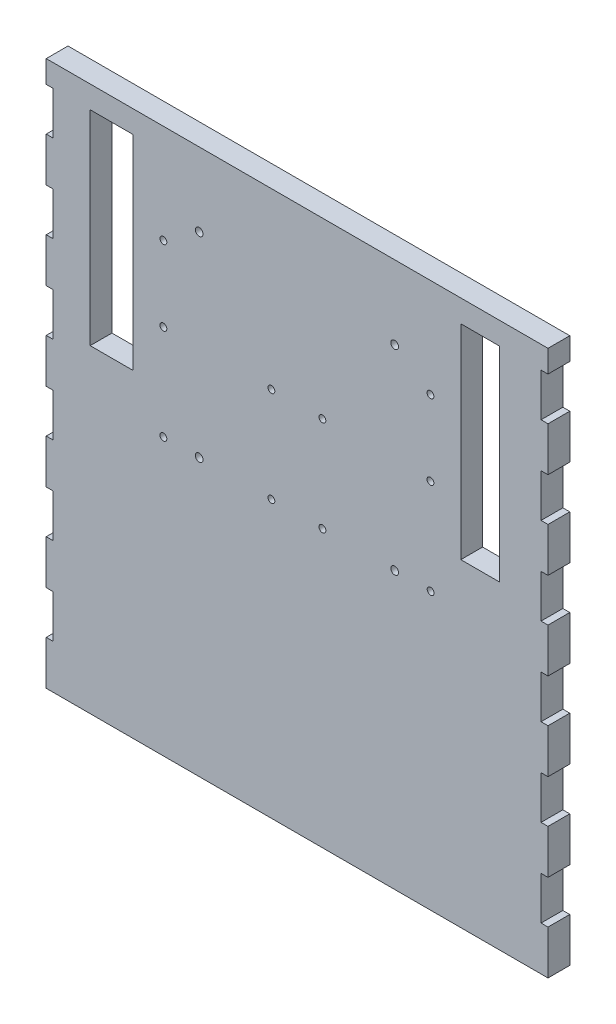
SolidWorks part; units mm, degrees
ref_plane "Front Plane" through (0, 0, 0) normal (0, 0, 1) x (1, 0, 0)
ref_plane "Top Plane" through (0, 0, 0) normal (0, 1, 0) x (1, 0, 0)
ref_plane "Right Plane" through (0, 0, 0) normal (1, 0, 0) x (0, 0, -1)
sketch "Model" plane through (0, 0, 0) normal (0, 0, 1) x (1, 0, 0)
  line L4 (-152.1412, 57.9109) -> (-132.3912, 57.9109)
  line L5 (-132.3912, 57.9109) -> (-132.3912, 151.6609)
  line L6 (-132.3912, 151.6609) -> (-152.1412, 151.6609)
  line L7 (-152.1412, 151.6609) -> (-152.1412, 57.9109)
  line L8 (17.9465, 57.9109) -> (35.6965, 57.9109)
  line L9 (35.6965, 57.9109) -> (35.6965, 151.6609)
  line L10 (35.6965, 151.6609) -> (17.9465, 151.6609)
  line L11 (17.9465, 151.6609) -> (17.9465, 57.9109)
  line L60 (57.9465, -88.3391) -> (57.9465, -68.0891)
  line L61 (57.9465, -68.0891) -> (54.7715, -68.0891)
  line L62 (54.7715, -68.0891) -> (54.7715, -48.3391)
  line L63 (54.7715, -48.3391) -> (57.9465, -48.3391)
  line L64 (57.9465, -48.3391) -> (57.9465, -28.0891)
  line L65 (57.9465, -28.0891) -> (54.7715, -28.0891)
  line L66 (54.7715, -28.0891) -> (54.7715, -8.3391)
  line L67 (54.7715, -8.3391) -> (57.9465, -8.3391)
  line L68 (57.9465, -8.3391) -> (57.9465, 11.9109)
  line L69 (57.9465, 11.9109) -> (54.7715, 11.9109)
  line L70 (54.7715, 11.9109) -> (54.7715, 31.6609)
  line L71 (54.7715, 31.6609) -> (57.9465, 31.6609)
  line L72 (57.9465, 31.6609) -> (57.9465, 51.9109)
  line L73 (57.9465, 51.9109) -> (54.7715, 51.9109)
  line L74 (54.7715, 51.9109) -> (54.7715, 71.6609)
  line L75 (54.7715, 71.6609) -> (57.9465, 71.6609)
  line L76 (57.9465, 71.6609) -> (57.9465, 91.9109)
  line L77 (57.9465, 91.9109) -> (54.7715, 91.9109)
  line L78 (54.7715, 91.9109) -> (54.7715, 111.6609)
  line L79 (54.7715, 111.6609) -> (57.9465, 111.6609)
  line L80 (57.9465, 111.6609) -> (57.9465, 131.9109)
  line L81 (57.9465, 131.9109) -> (54.7715, 131.9109)
  line L82 (54.7715, 131.9109) -> (54.7715, 151.6609)
  line L83 (54.7715, 151.6609) -> (57.9465, 151.6609)
  line L84 (57.9465, 151.6609) -> (57.9465, 161.9109)
  line L85 (57.9465, 161.9109) -> (-172.3035, 161.9109)
  line L86 (-172.3035, 161.9109) -> (-172.3035, 151.6609)
  line L87 (-172.3035, 151.6609) -> (-169.1285, 151.6609)
  line L88 (-169.1285, 151.6609) -> (-169.1285, 131.9109)
  line L89 (-169.1285, 131.9109) -> (-172.3035, 131.9109)
  line L90 (-172.3035, 131.9109) -> (-172.3035, 111.6609)
  line L91 (-172.3035, 111.6609) -> (-169.1285, 111.6609)
  line L92 (-169.1285, 111.6609) -> (-169.1285, 91.9109)
  line L93 (-169.1285, 91.9109) -> (-172.3035, 91.9109)
  line L94 (-172.3035, 91.9109) -> (-172.3035, 71.6609)
  line L95 (-172.3035, 71.6609) -> (-169.1285, 71.6609)
  line L96 (-169.1285, 71.6609) -> (-169.1285, 51.9109)
  line L97 (-169.1285, 51.9109) -> (-172.3035, 51.9109)
  line L98 (-172.3035, 51.9109) -> (-172.3035, 31.6609)
  line L99 (-172.3035, 31.6609) -> (-169.1285, 31.6609)
  line L100 (-169.1285, 31.6609) -> (-169.1285, 11.9109)
  line L101 (-169.1285, 11.9109) -> (-172.3035, 11.9109)
  line L102 (-172.3035, 11.9109) -> (-172.3035, -8.3391)
  line L103 (-172.3035, -8.3391) -> (-169.1285, -8.3391)
  line L104 (-169.1285, -8.3391) -> (-169.1285, -28.0891)
  line L105 (-169.1285, -28.0891) -> (-172.3035, -28.0891)
  line L106 (-172.3035, -28.0891) -> (-172.3035, -48.3391)
  line L107 (-172.3035, -48.3391) -> (-169.1285, -48.3391)
  line L108 (-169.1285, -48.3391) -> (-169.1285, -68.0891)
  line L109 (-169.1285, -68.0891) -> (-172.3035, -68.0891)
  line L110 (-172.3035, -68.0891) -> (-172.3035, -88.3391)
  line L111 (-172.3035, -88.3391) -> (57.9465, -88.3391)
  circle A14 centre (-12.414, 38.4299) radius 1.775
  circle A15 centre (4.0963, 38.4299) radius 1.575
  circle A16 centre (4.0086, 82.125) radius 1.575
  circle A17 centre (-45.5601, 82.125) radius 1.575
  circle A18 centre (-45.5601, 38.4299) radius 1.575
  circle A19 centre (-68.9723, 38.4299) radius 1.575
  circle A20 centre (-68.9723, 82.125) radius 1.575
  circle A21 centre (-102.1184, 38.4299) radius 1.775
  circle A22 centre (-118.541, 38.4299) radius 1.575
  circle A23 centre (-118.541, 82.125) radius 1.575
  circle A24 centre (-118.541, 116.5476) radius 1.575
  circle A25 centre (-102.1184, 128.1299) radius 1.775
  circle A26 centre (-12.414, 128.1299) radius 1.775
  circle A27 centre (4.0086, 116.5476) radius 1.575
extrude "Boss-Extrude1" add sketch "Model" along normal blind 10
